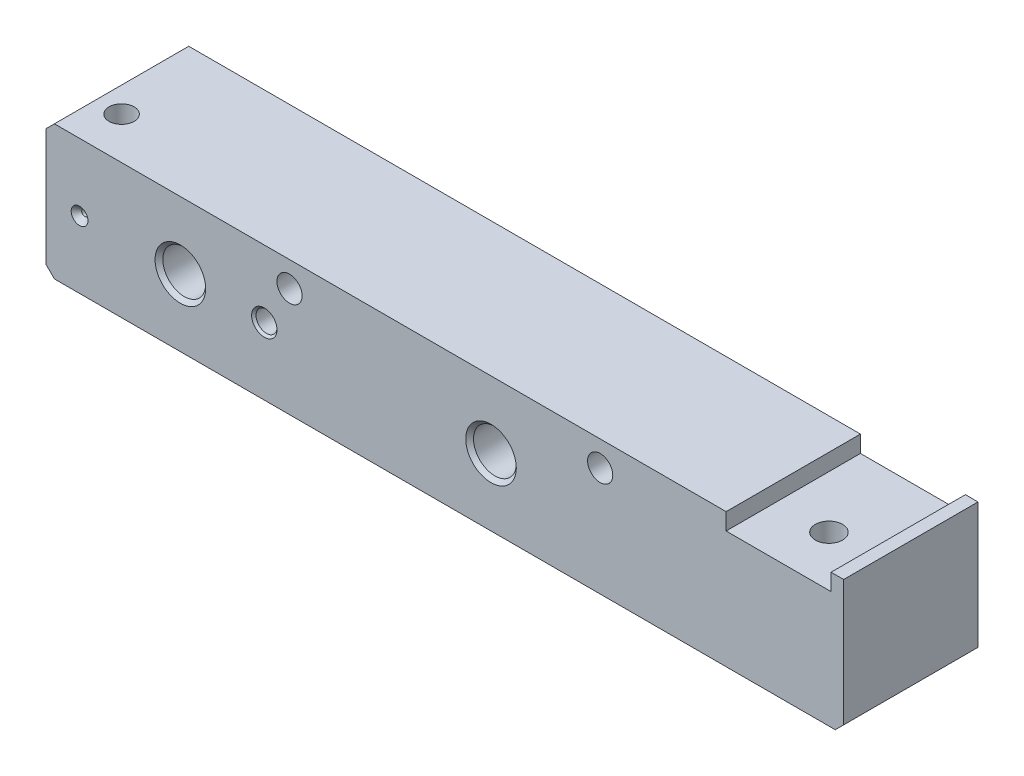
SolidWorks part; units mm, degrees
material "Chrome Stainless Steel"
ref_plane "Front Plane" through (0, 0, 0) normal (0, 0, 1) x (1, 0, 0)
ref_plane "Top Plane" through (0, 0, 0) normal (0, 1, 0) x (1, 0, 0)
ref_plane "Right Plane" through (0, 0, 0) normal (1, 0, 0) x (0, 0, -1)
sketch "Sketch1" plane through (0, 0, 0) normal (0, 0, 1) x (1, 0, 0)
  line L0 (67, 12) -> (92, 12)
  line L1 (-93, 16) -> (67, 16)
  line L2 (-95, 14) -> (-95, -14)
  line L3 (-93, -16) -> (93, -16)
  line L4 (95, 16) -> (95, -14)
  line L5 (92, 16) -> (92, 12)
  line L6 (67, 16) -> (67, 12)
  line L7 (-95, 12) -> (95, 12) construction
  line L8 (92, 16) -> (95, 16)
  line L9 (-95, 16) -> (95, 16) construction
  line L10 (67, 16) -> (67, -11) construction
  line L11 (92, 16) -> (92, -11) construction
  line L12 (95, 16) -> (95, -11) construction
  line L13 (93, -16) -> (95, -14)
  line L14 (-95, -14) -> (-93, -16)
  line L15 (-95, 14) -> (-93, 16)
  point P0 (0, 0)
  point P3 (-95, -16)
  dimension "D2" = 95
  dimension "D3" = 2
  dimension "D4" = 32
  dimension "D8" = 2
  dimension "D9" = 45
  dimension "D10" = 45
  dimension "D11" = 2
  dimension "D12" = 45
  dimension "D13" = 190
  dimension "D14" = 16
  dimension "D5" = 4
  dimension "D6" = 3
  dimension "D7" = 25
extrude "Boss-Extrude1" add sketch "Sketch1" along normal mid plane 32
sketch "Sketch2" plane through (0, 0, 16) normal (0, 0, 1) x (1, 0, 0)
  line L0 (-95, 0) -> (95, 0) construction
  line L1 (-95, 14) -> (-95, -14) construction
  line L2 (95, -14) -> (95, 16) construction
  line L3 (11, 16) -> (11, -16) construction
  line L4 (67, 16) -> (-93, 16) construction
  line L5 (-93, -16) -> (93, -16) construction
  line L6 (-63, 16) -> (-63, -16) construction
  line L7 (67, 12) -> (67, 16) construction
  dimension "D2" = 56
  dimension "D1" = 74
hole_wizard "M12 Tapped Hole2" positions "Sketch8" profile "Sketch7" tap size "M12" standard "ISO"
sketch "Sketch8" plane through (0, 0, 16) normal (0, 0, 1) x (1, 0, 0)
  line L0 (-63, 16) -> (-63, -16) construction
  line L1 (11, 16) -> (11, -16) construction
  point P0 (-63, 0)
  point P4 (11, 0)
sketch "Sketch7" plane through (-63, 0, 16) normal (1, 0, 0) x (0, -1, 0)
  line L0 (0, 0) -> (0, 27.0644)
  line L1 (0, 27.0644) -> (5.1, 24)
  line L2 (5.1, 24) -> (5.1, 0.925)
  line L3 (5.1, 0.925) -> (6.025, 0)
  line L5 (6.025, 0) -> (0, 0)
  line L6 (-5.1, 0.925) -> (-6.025, 0) construction
  line L10 (0, 27.0644) -> (-5.1, 24) construction
  line L11 (0, -6.35) -> (0, 107.95) construction
  dimension "Tap Drill Dia." = 10.2
  dimension "Tap Drill Depth" = 24
  dimension "Near C'Sink Dia." = 12.05
  dimension "Near C'Sink Angle" = 90
  dimension "Drill Angle" = 118
cosmetic thread "Hole Thread5" parameters "D1"=24, "D2"=12
cosmetic thread "Hole Thread6" parameters "D1"=24, "D2"=12
sketch "Sketch9" plane through (0, -16, 0) normal (0, -1, 0) x (1, 0, 0)
  line L0 (-63, -8) -> (-63, 16) construction
  line L1 (-57.9, -8) -> (-68.1, -8) construction
  line L2 (-95, 16) -> (95, 16) construction
  line L3 (11, -8) -> (11, 16) construction
  line L4 (16.1, -8) -> (5.9, -8) construction
  line L5 (-63, 4) -> (11, 4) construction
hole_wizard "M4 Tapped Hole1" positions "Sketch10" profile "Sketch11" tap size "M4" standard "ISO"
sketch "Sketch10" plane through (0, -16, 0) normal (0, -1, 0) x (-1, 0, 0)
  point P0 (-11, -4)
  point P3 (63, -4)
sketch "Sketch11" plane through (11, -16, 4) normal (1, 0, 0) x (0, 0, -1)
  line L0 (0, 0) -> (0, 12.4914)
  line L1 (0, 12.4914) -> (1.65, 11.5)
  line L2 (1.65, 11.5) -> (1.65, 0.375)
  line L3 (1.65, 0.375) -> (2.025, 0)
  line L5 (2.025, 0) -> (0, 0)
  line L6 (-1.65, 0.375) -> (-2.025, 0) construction
  line L10 (0, 12.4914) -> (-1.65, 11.5) construction
  line L11 (0, -6.35) -> (0, 107.95) construction
  dimension "Tap Drill Dia." = 3.3
  dimension "Tap Drill Depth" = 11.5
  dimension "Near C'Sink Dia." = 4.05
  dimension "Near C'Sink Angle" = 90
  dimension "Drill Angle" = 118
cosmetic thread "Hole Thread7" parameters "D1"=8, "D2"=4
cosmetic thread "Hole Thread8" parameters "D1"=8, "D2"=4
sketch "Sketch12" plane through (0, -16, 0) normal (0, -1, 0) x (1, 0, 0)
  line L0 (77.5, -16) -> (77.5, 4) construction
  line L1 (-93, -16) -> (93, -16) construction
  line L3 (77.5, 4) -> (93, 4) construction
  line L4 (93, 16) -> (93, -16) construction
  dimension "D1" = 15.5
  dimension "D2" = 20
sketch "Sketch15" plane through (0, -16, 0) normal (0, -1, 0) x (1, 0, 0)
  line L0 (-63, 4) -> (-87, 4) construction
  line L1 (-87, 4) -> (-87, 16) construction
  line L2 (-95, 16) -> (95, 16) construction
  line L3 (-93, -16) -> (93, -16) construction
  circle A0 centre (-87, 6) radius 3
  dimension "D3" = 6
  dimension "D1" = 22
  dimension "D2" = 24
extrude "Cut-Extrude1" cut sketch "Sketch15" against normal through all
hole_wizard "CSK for M4 Countersunk Flat Head Screw1" positions "Sketch17" profile "Sketch18" countersink size "M4" standard "ISO"
sketch "Sketch17" plane through (0, 0, 16) normal (0, 0, 1) x (1, 0, 0)
  line L0 (-95, 0) -> (95, 0) construction
  point P0 (-87, 0)
  dimension "D1" = 24
sketch "Sketch18" plane through (-87, 0, 16) normal (1, 0, 0) x (0, -1, 0)
  line L0 (0, 0) -> (0, 10.4506)
  line L1 (0, 10.4506) -> (0.75, 10)
  line L2 (0.75, 10) -> (0.75, 1.25)
  line L3 (0.75, 1.25) -> (2, 0)
  line L5 (2, 0) -> (0, 0)
  line L6 (-0.75, 1.25) -> (-2, 0) construction
  line L10 (0, 10.4506) -> (-0.75, 10) construction
  line L11 (0, -6.35) -> (0, 107.95) construction
  dimension "Hole Dia." = 1.5
  dimension "Hole Depth" = 10
  dimension "Near C'Sink Dia." = 4
  dimension "Near C'Sink Angle" = 90
  dimension "Drill Angle" = 118
hole_wizard "M6 Tapped Hole1" positions "Sketch19" profile "Sketch21" tap size "M6" standard "ISO"
sketch "Sketch19" plane through (0, 0, 16) normal (0, 0, 1) x (1, 0, 0)
  line L0 (-95, 0) -> (95, 0) construction
  point P0 (-43, 0)
  dimension "D1" = 20
sketch "Sketch21" plane through (-43, 0, 16) normal (1, 0, 0) x (0, -1, 0)
  line L0 (0, 0) -> (0, 17.5022)
  line L1 (0, 17.5022) -> (2.5, 16)
  line L2 (2.5, 16) -> (2.5, 0.525)
  line L3 (2.5, 0.525) -> (3.025, 0)
  line L5 (3.025, 0) -> (0, 0)
  line L6 (-2.5, 0.525) -> (-3.025, 0) construction
  line L10 (0, 17.5022) -> (-2.5, 16) construction
  line L11 (0, -6.35) -> (0, 107.95) construction
  dimension "Tap Drill Dia." = 5
  dimension "Tap Drill Depth" = 16
  dimension "Near C'Sink Dia." = 6.05
  dimension "Near C'Sink Angle" = 90
  dimension "Drill Angle" = 118
cosmetic thread "Hole Thread9" parameters "D1"=12, "D2"=6
sketch "Sketch22" plane through (0, 0, 16) normal (0, 0, 1) x (1, 0, 0)
  line L0 (-95, 14) -> (-95, -14) construction
  line L1 (67, 16) -> (-93, 16) construction
  circle A0 centre (-37, 10) radius 3
  circle A1 centre (37, 10) radius 3
  dimension "D4" = 6
  dimension "D1" = 74
  dimension "D2" = 58
  dimension "D3" = 6
extrude "Cut-Extrude2" cut sketch "Sketch22" against normal through all
hole_wizard "CSK for M10 Countersunk Flat Head Screw2" positions "Sketch27" profile "Sketch28" countersink size "M10" standard "ISO"
sketch "Sketch27" plane through (0, -16, 0) normal (0, -1, 0) x (-1, 0, 0)
  line L0 (93, 16) -> (-93, 16) construction
  line L1 (-92, 16) -> (-92, -16) construction
  line L2 (93, -16) -> (-93, -16) construction
  point P0 (-79.5, -4)
  dimension "D1" = 20
  dimension "D2" = 12.5
sketch "Sketch28" plane through (79.5, -16, 4) normal (1, 0, 0) x (0, 0, -1)
  line L0 (0, 0) -> (0, 33.9528)
  line L1 (0, 33.9528) -> (3.25, 32)
  line L2 (3.25, 32) -> (3.25, 3.25)
  line L3 (3.25, 3.25) -> (6.5, 0)
  line L5 (6.5, 0) -> (0, 0)
  line L6 (-3.25, 3.25) -> (-6.5, 0) construction
  line L10 (0, 33.9528) -> (-3.25, 32) construction
  line L11 (0, -6.35) -> (0, 107.95) construction
  dimension "Hole Dia." = 6.5
  dimension "Hole Depth" = 32
  dimension "Near C'Sink Dia." = 13
  dimension "Near C'Sink Angle" = 90
  dimension "Drill Angle" = 118
